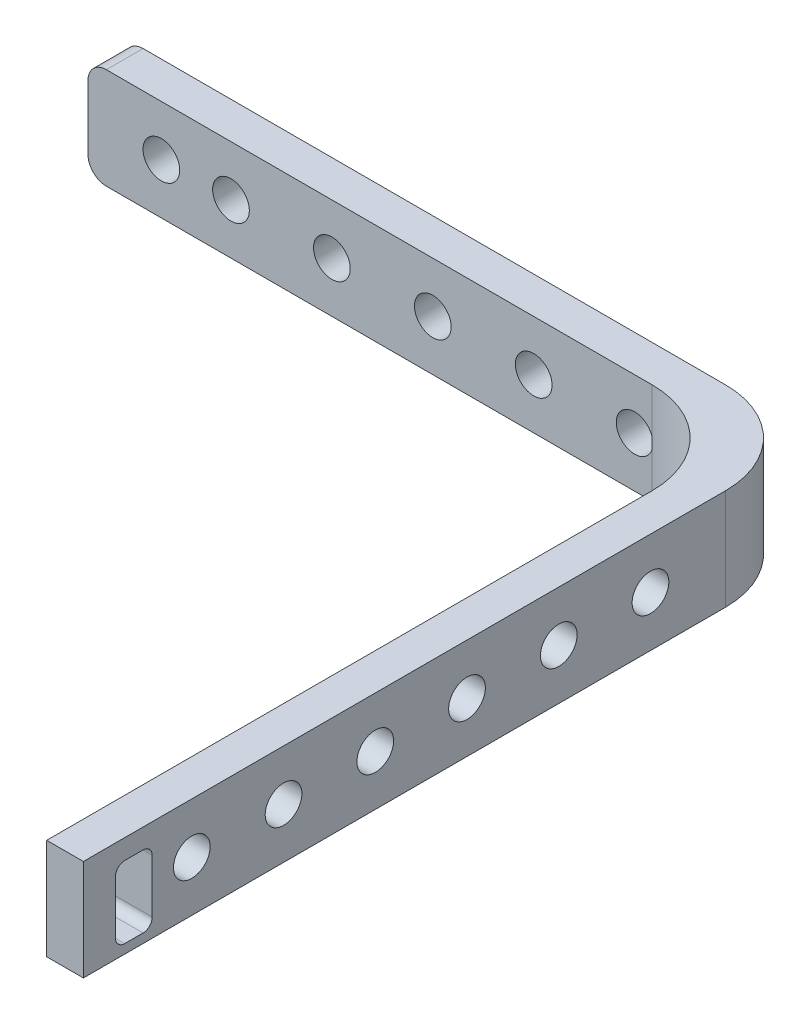
SolidWorks part; units mm, degrees
ref_plane "Front Plane" through (0, 0, 0) normal (0, 0, 1) x (1, 0, 0)
ref_plane "Top Plane" through (0, 0, 0) normal (0, 1, 0) x (1, 0, 0)
ref_plane "Right Plane" through (0, 0, 0) normal (1, 0, 0) x (0, 0, -1)
sketch "Sketch2" plane through (0, 0, 0) normal (0, 0, 1) x (1, 0, 0)
  line L0 (0, 0) -> (71.5, 0)
  line L1 (71.5, 0) -> (71.5, 11)
  line L2 (71.5, 11) -> (0, 11)
  line L3 (0, 11) -> (0, 0)
extrude "Boss-Extrude2" add sketch "Sketch2" along normal blind 4
sketch "Sketch3" plane through (0, 0, 4) normal (0, 0, 1) x (1, 0, 0)
  circle A0 centre (8, 5.5) radius 2
extrude "Cut-Extrude1" cut sketch "Sketch3" against normal blind 4
sketch "Sketch4" plane through (0, 11, 0) normal (0, 1, 0) x (1, 0, 0)
  line L0 (71.5, 0) -> (75.5, 0)
  line L1 (75.5, 0) -> (75.5, -4)
  line L2 (75.5, -4) -> (71.5, -4)
  line L3 (71.5, -4) -> (71.5, 0)
extrude "Boss-Extrude3" add sketch "Sketch4" against normal blind 11
sketch "Sketch5" plane through (0, 0, 4) normal (0, 0, 1) x (1, 0, 0)
  line L0 (75.5, 11) -> (71.5, 11)
  line L1 (75.5, 11) -> (0, 11) construction
  line L2 (71.5, 11) -> (71.5, 0)
  line L3 (0, 0) -> (75.5, 0) construction
  line L4 (71.5, 0) -> (75.5, 0)
  line L5 (75.5, 0) -> (75.5, 11)
extrude "Boss-Extrude4" add sketch "Sketch5" along normal blind 76
sketch "Sketch6" plane through (75.5, 0, 0) normal (1, 0, 0) x (0, 0, -1)
  line L2 (-75.5, 1) -> (-73.5, 1)
  line L4 (-75.5, 8.8386) -> (-73.5, 8.8386)
  line L6 (-76.5, 2) -> (-76.5, 7.8386)
  line L8 (-72.5, 2) -> (-72.5, 7.8386)
  arc A1 (-76.5, 7.8386) -> (-75.5, 8.8386) centre (-75.5, 7.8386) cw
  arc A2 (-73.5, 8.8386) -> (-72.5, 7.8386) centre (-73.5, 7.8386) cw
  arc A3 (-72.5, 2) -> (-73.5, 1) centre (-73.5, 2) cw
  arc A4 (-76.5, 2) -> (-75.5, 1) centre (-75.5, 2) ccw
  point P13 (-72.5, 5.5)
  point P14 (-76.5, 5.5)
  dimension "D1" = 1
extrude "Cut-Extrude2" cut sketch "Sketch6" against normal up to surface (4 mm away) up to face at (71.5, 5.5, 42)
fillet "Fillet1" radius 10 1 edges at (71.5, 5.5, 4)
fillet "Fillet2" radius 10 1 edges at (75.5, 5.5, 0)
fillet "Fillet4" radius 2 2 edges at (0, 0, 2) (0, 11, 2)
sketch "Sketch7" plane through (0, 0, 0) normal (0, 0, -1) x (-1, 0, 0)
  circle A1 centre (-15.5887, 5.5) radius 2
  circle A2 centre (-26.5887, 5.5) radius 2
  circle A3 centre (-37.5887, 5.5) radius 2
  circle A4 centre (-48.5887, 5.5) radius 2
  circle A5 centre (-59.5887, 5.5) radius 2
  dimension "D1" = 5
extrude "Cut-Extrude3" cut sketch "Sketch7" against normal up to surface (4 mm away) up to face at (21.0286, 5.5, 4)
sketch "Sketch8" plane through (71.5, 0, 0) normal (-1, 0, 0) x (0, 0, 1)
  circle A0 centre (18.182, 5.5) radius 2
  circle A1 centre (28.182, 5.5) radius 2
  circle A2 centre (38.182, 5.5) radius 2
  circle A3 centre (48.182, 5.5) radius 2
  circle A4 centre (58.182, 5.5) radius 2
  circle A5 centre (68.182, 5.5) radius 2
  dimension "D1" = 6
extrude "Cut-Extrude4" cut sketch "Sketch8" against normal up to surface (4 mm away) up to face at (75.5, 4.9193, 74.5)
